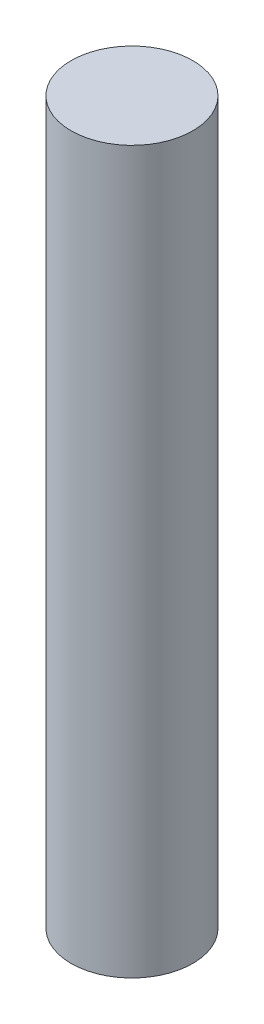
SolidWorks part; units mm, degrees
ref_plane "Front Plane" through (0, 0, 0) normal (0, 0, 1) x (1, 0, 0)
ref_plane "Top Plane" through (0, 0, 0) normal (0, 1, 0) x (1, 0, 0)
ref_plane "Right Plane" through (0, 0, 0) normal (1, 0, 0) x (0, 0, -1)
sketch "Sketch1" plane through (0, 0, 0) normal (0, 0, 1) x (1, 0, 0)
  line L0 (0, 0) -> (0, 80)
  point P6 (0, 80)
  dimension "D2" = 80
sketch "Sketch2" plane through (0, 0, 0) normal (0, 1, 0) x (1, 0, 0)
  circle A0 centre (0, 0) radius 6.75
  dimension "D1" = 13.5
sweep "Sweep1" add profiles "Sketch2" path "Sketch1"
